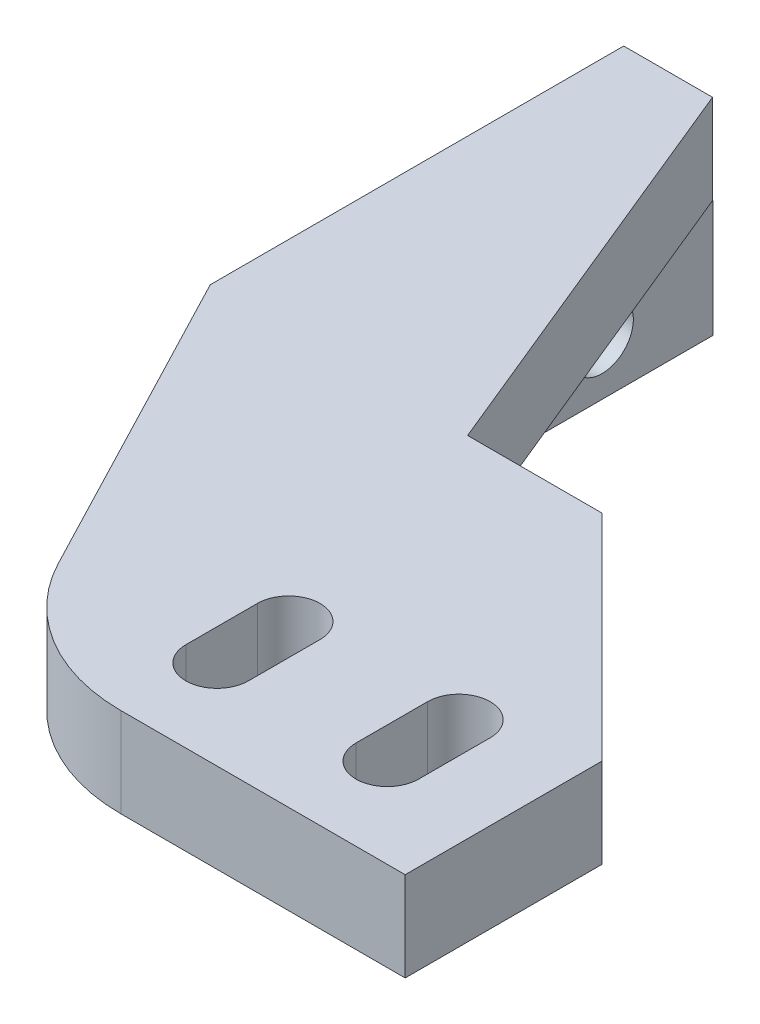
SolidWorks part; units mm, degrees
ref_plane "Piano frontale" through (0, 0, 0) normal (0, 0, 1) x (1, 0, 0)
ref_plane "Piano superiore" through (0, 0, 0) normal (0, 1, 0) x (1, 0, 0)
ref_plane "Piano destro" through (0, 0, 0) normal (1, 0, 0) x (0, 0, -1)
ref_plane "Piano1" through (0, 40, 0) normal (0, 1, 0) x (1, 0, 0)
sketch "Schizzo18" plane through (0, 40, 0) normal (0, 1, 0) x (1, 0, 0)
  line L0 (25, -16) -> (-9, -16)
  line L1 (25, -16) -> (25, 7)
  line L2 (25, 7) -> (5.4879, 7)
  line L3 (-9, 30.2124) -> (-4.0369, 30.2124)
  line L4 (-9, -16) -> (-9, 30.2124)
  line L5 (-4.0369, 30.2124) -> (5.4879, 7)
  line L6 (19, -16) -> (19, 7) construction
  line L7 (-9, -28.4145) -> (-9, 27.2974) construction
  line L8 (29.4558, 7) -> (-19.1855, 7) construction
  line L9 (25, -28.4145) -> (25, 27.2974) construction
  line L10 (29.4558, -16) -> (-19.1855, -16) construction
  line L11 (25, -11) -> (-9, -11) construction
  line L12 (25, -7) -> (-9, -7) construction
  line L13 (19, -11) -> (19, -7) construction
  line L14 (17.25, -11) -> (17.25, -7)
  line L15 (20.75, -11) -> (20.75, -7)
  line L16 (9.4906, -11) -> (9.4906, -7) construction
  line L17 (7.7406, -11) -> (7.7406, -7)
  line L18 (11.2406, -11) -> (11.2406, -7)
  arc A0 (17.25, -11) -> (20.75, -11) centre (19, -11) ccw
  arc A1 (20.75, -7) -> (17.25, -7) centre (19, -7) ccw
  arc A2 (7.7406, -11) -> (11.2406, -11) centre (9.4906, -11) ccw
  arc A3 (11.2406, -7) -> (7.7406, -7) centre (9.4906, -7) ccw
  point P22 (19, -9)
  point P29 (9.4906, -9)
  dimension "D1" = 6
  dimension "D2" = 23
  dimension "D3" = 34
  dimension "D4" = 5
  dimension "D5" = 4
extrude "Estrusione-Estrusione8" add sketch "Schizzo18" along normal blind 5 separate body
sketch "Schizzo19" plane through (0, 40, 0) normal (0, -1, 0) x (1, 0, 0)
  line L0 (-4.0369, -30.2124) -> (-9, -30.2124) construction
  line L1 (-9, 16) -> (-4, 16)
  line L2 (-9, 16) -> (-9, -30.2124)
  line L3 (-9, -30.2124) -> (-4, -30.2124)
  line L4 (-4, 16) -> (-4, -30.2124)
  dimension "D1" = 5
extrude "Estrusione-Estrusione9" add sketch "Schizzo19" along normal blind 6.5
sketch "Schizzo20" plane through (-9, 0, 0) normal (-1, 0, 0) x (0, 0, 1)
  line L0 (9, 45) -> (9, 33.5) construction
  line L1 (11, 45) -> (7, 45) construction
  line L2 (16, 33.5) -> (-30.2124, 33.5) construction
  line L3 (-19, 45) -> (-19, 33.5) construction
  line L4 (-24, 45) -> (-24, 33.5) construction
  line L13 (-14, 45) -> (-14, 33.5) construction
  line L14 (-23.6103, 33.5) -> (25.3232, 33.5) construction
  line L15 (-23.6103, 36.5) -> (25.3232, 36.5) construction
  circle A0 centre (-24, 36.5) radius 1.75
  circle A1 centre (-14, 36.5) radius 1.75
  dimension "D1" = 28
  dimension "D2" = 5
  dimension "D3" = 5
  dimension "D4" = 3
extrude "Taglio-Estrusione9" cut sketch "Schizzo20" against normal blind 6
sketch "Schizzo21" plane through (-9, 0, 0) normal (-1, 0, 0) x (0, 0, 1)
  line L0 (16, 23.2712) -> (16, 48.2769) construction
  line L1 (1, 23.2712) -> (1, 48.2769) construction
  line L2 (16, 45) -> (16, 40.1473)
  dimension "D1" = 15
sketch "Schizzo24" plane through (0, 45, 0) normal (0, 1, 0) x (1, 0, 0)
  line L0 (-9, -16) -> (25, -16) construction
  line L2 (3.0423, -16) -> (-9, 7.1062)
  line L3 (-9, 30.2124) -> (-9, -16) construction
  line L4 (-9, 7.1062) -> (-9, -16)
  line L5 (-9, -16) -> (3.0423, -16)
extrude "Taglio-Estrusione13" cut sketch "Schizzo24" against normal blind 21
ref_plane "Piano2" through (0, 0, -7.1062) normal (0, 0, 1) x (1, 0, 0)
sketch "Schizzo26" plane through (0, 0, -7.1062) normal (0, 0, 1) x (1, 0, 0)
  line L0 (-9, 23.2712) -> (-9, 48.2769) construction
  line L1 (-4, 33.5) -> (-9, 33.5)
  line L2 (-4, 33.5) -> (-4, 40)
  line L3 (-4, 40) -> (-9, 40)
  line L4 (-9, 33.5) -> (-9, 40)
  line L5 (18.7, 40) -> (-18.7, 40) construction
extrude "Taglio-Estrusione15" cut sketch "Schizzo26" along normal blind 21
fillet "Raccordo1" radius 10 2 edges at (3.0423, 42.5, 16)
chamfer "Smusso1" distance 12 angle 45 1 edges at (25, 42.5, -7)
